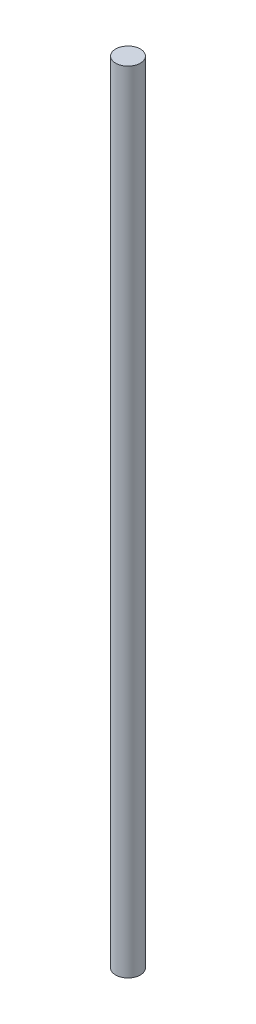
SolidWorks part; units mm, degrees
ref_plane "Front Plane" through (0, 0, 0) normal (0, 0, 1) x (1, 0, 0)
ref_plane "Top Plane" through (0, 0, 0) normal (0, 1, 0) x (1, 0, 0)
ref_plane "Right Plane" through (0, 0, 0) normal (1, 0, 0) x (0, 0, -1)
sketch "Sketch1" plane through (0, 0, 0) normal (0, 1, 0) x (1, 0, 0)
  circle A0 centre (0, 0) radius 6.35
  dimension "D1" = 12.7
extrude "Boss-Extrude1" add sketch "Sketch1" along normal blind 406.4
ref_plane "Plane1" through (0, 406.4, 0) normal (0, 1, 0) x (1, 0, 0)
ref_plane "Plane2" through (0, 419.1, 0) normal (0, 1, 0) x (1, 0, 0)
ref_point "Point1"
ref_point "Point2"
